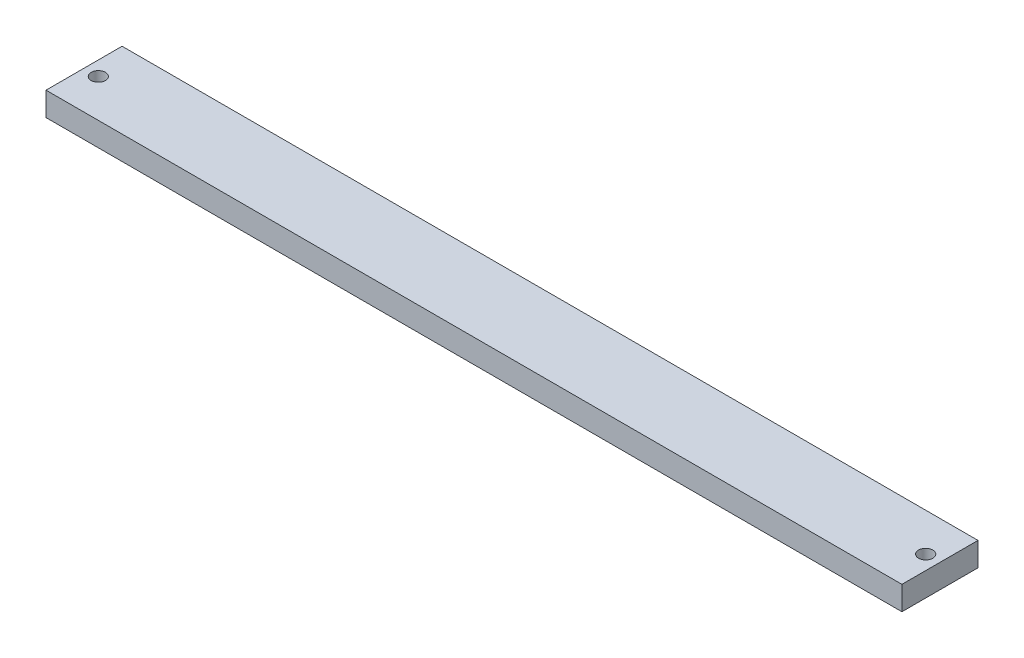
SolidWorks part; units mm, degrees
material "Trupan"
ref_plane "Alzado" through (0, 0, 0) normal (0, 0, 1) x (1, 0, 0)
ref_plane "Planta" through (0, 0, 0) normal (0, 1, 0) x (1, 0, 0)
ref_plane "Vista lateral" through (0, 0, 0) normal (1, 0, 0) x (0, 0, -1)
sketch "Croquis1" plane through (0, 0, 0) normal (0, 1, 0) x (1, 0, 0)
  line L1 (90, -8) -> (-90, -8)
  line L2 (90, -8) -> (90, 8)
  line L3 (90, 8) -> (-90, 8)
  line L4 (-90, -8) -> (-90, 8)
  line L5 (90, -8) -> (-90, 8) construction
  line L6 (90, 8) -> (-90, -8) construction
  point P0 (0, 0)
  dimension "D1" = 16
  dimension "D2" = 180
extrude "Saliente-Extruir1" add sketch "Croquis1" along normal blind 5
sketch "Croquis2" plane through (0, 0, 0) normal (0, -1, 0) x (1, 0, 0)
  line L0 (-90, -8) -> (-90, 8) construction
  line L1 (90, -8) -> (-90, -8) construction
  circle A0 centre (-87, 0) radius 1.5
  dimension "D1" = 3
  dimension "D2" = 3
  dimension "D3" = 8
extrude "Cortar-Extruir1" cut sketch "Croquis2" against normal through all
mirror "Simetría1" about plane through (0, 0, 0) normal (1, 0, 0) of "Cortar-Extruir1"
